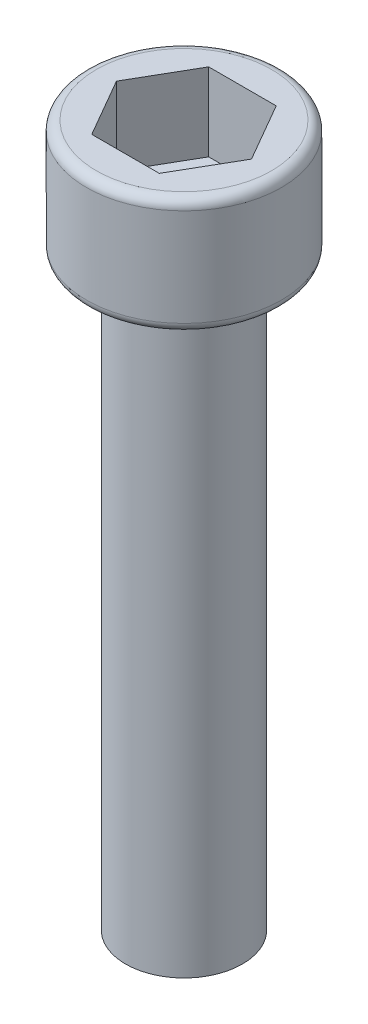
SolidWorks part; units mm, degrees
material "Galvanized Steel"
ref_plane "Front Plane" through (0, 0, 0) normal (0, 0, 1) x (1, 0, 0)
ref_plane "Top Plane" through (0, 0, 0) normal (0, 1, 0) x (1, 0, 0)
ref_plane "Right Plane" through (0, 0, 0) normal (1, 0, 0) x (0, 0, -1)
sketch "Sketch1" plane through (0, 0, 0) normal (0, 0, 1) x (1, 0, 0)
  line L0 (0, -9) -> (1.5, -9)
  line L1 (1.5, -9) -> (1.5, 6)
  line L2 (1.5, 6) -> (2.5, 6)
  line L3 (2.5, 6) -> (2.5, 9)
  line L4 (2.5, 9) -> (0, 9)
  line L5 (0, 9) -> (0, -9)
  line L6 (0, -1000) -> (0, 49000) construction
  point P2 (0, 0)
  dimension "D1" = 3
  dimension "D2" = 5
  dimension "D3" = 3
  dimension "D4" = 15
revolve "Revolve1" add sketch "Sketch1" angle 360 about L6
sketch "Sketch2" plane through (0, 9, 0) normal (0, 1, 0) x (1, 0, 0)
  line L1 (0.866, 1.5) -> (-0.866, 1.5)
  line L2 (-0.866, 1.5) -> (-1.7321, 0)
  line L3 (-1.7321, 0) -> (-0.866, -1.5)
  line L4 (-0.866, -1.5) -> (0.866, -1.5)
  line L5 (0.866, -1.5) -> (1.7321, 0)
  line L6 (1.7321, 0) -> (0.866, 1.5)
  circle A0 centre (0, 0) radius 1.5 construction
  dimension "D1" = 3
extrude "Cut-Extrude1" cut sketch "Sketch2" against normal blind 2
fillet "Fillet1" radius 0.25 2 edges at (2.5, 6, 0) (2.5, 9, 0)
